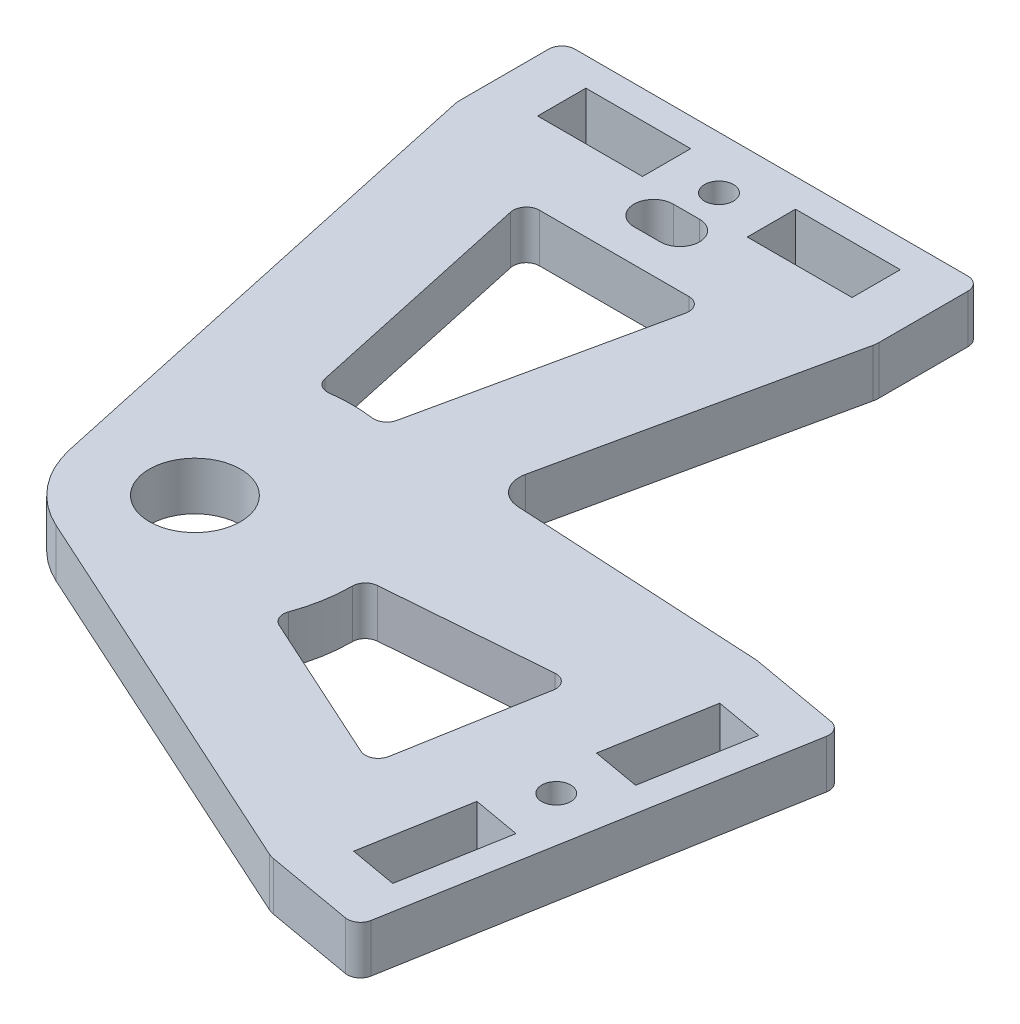
SolidWorks part; units mm, degrees
ref_plane "Front Plane" through (0, 0, 0) normal (0, 0, 1) x (1, 0, 0)
ref_plane "Top Plane" through (0, 0, 0) normal (0, 1, 0) x (1, 0, 0)
ref_plane "Right Plane" through (0, 0, 0) normal (1, 0, 0) x (0, 0, -1)
sketch "Sketch1" plane through (0, 0, 0) normal (0, 1, 0) x (1, 0, 0)
  line L0 (0, 0) -> (53.155, -9.3727) construction
  line L1 (0, 0) -> (0, 63.5) construction
  line L2 (12.7, 63.5) -> (-12.7, 63.5) construction
  line L3 (6.35, 63.5) -> (19.05, 63.5) construction
  line L4 (-6.35, 60.579) -> (-19.05, 60.579)
  line L5 (-6.35, 60.579) -> (-6.35, 66.421)
  line L6 (-6.35, 66.421) -> (-19.05, 66.421)
  line L7 (-19.05, 60.579) -> (-19.05, 66.421)
  line L8 (-12.7, 66.421) -> (-12.7, 60.579) construction
  line L9 (-6.35, 63.5) -> (-19.05, 63.5) construction
  line L10 (12.7, 66.421) -> (12.7, 60.579) construction
  line L11 (19.05, 60.579) -> (19.05, 66.421)
  line L12 (6.35, 66.421) -> (19.05, 66.421)
  line L13 (6.35, 60.579) -> (6.35, 66.421)
  line L14 (6.35, 60.579) -> (19.05, 60.579)
  line L15 (50.9497, -21.8797) -> (55.3603, 3.1344) construction
  line L16 (53.6034, 9.9916) -> (51.364, -2.7084)
  line L17 (53.6034, 9.9916) -> (59.3566, 8.9772)
  line L18 (51.364, -2.7084) -> (57.1173, -3.7228)
  line L19 (59.3566, 8.9772) -> (57.1173, -3.7228)
  line L20 (53.6034, 9.9916) -> (57.1173, -3.7228) construction
  line L21 (51.364, -2.7084) -> (59.3566, 8.9772) construction
  line L22 (49.1927, -15.0225) -> (52.7066, -28.7369) construction
  line L23 (46.9534, -27.7225) -> (54.946, -16.0369) construction
  line L24 (52.7066, -28.7369) -> (54.946, -16.0369)
  line L25 (49.1927, -15.0225) -> (54.946, -16.0369)
  line L26 (46.9534, -27.7225) -> (52.7066, -28.7369)
  line L27 (46.9534, -27.7225) -> (49.1927, -15.0225)
  line L28 (-25.4, 57.15) -> (-12.411, -2.6938)
  line L29 (-4.0407, 18.6165) -> (-11.026, 50.8)
  line L30 (25.4, 57.15) -> (25.4, 69.85)
  line L31 (25.4, 69.85) -> (-25.4, 69.85)
  line L32 (-25.4, 57.15) -> (-25.4, 69.85)
  line L33 (0, 69.85) -> (0, 63.5) construction
  line L34 (25.4, 63.5) -> (-25.4, 63.5) construction
  line L35 (25.4, 57.15) -> (17.0312, 18.5928)
  line L36 (4.0407, 18.6165) -> (11.026, 50.8)
  line L37 (-11.026, 50.8) -> (11.026, 50.8)
  line L38 (54.9979, -35.4894) -> (63.8192, 14.5388)
  line L39 (54.9979, -35.4894) -> (42.4908, -33.2841)
  line L40 (63.8192, 14.5388) -> (51.3121, 16.7441)
  line L42 (54.9979, -35.4894) -> (51.3121, 16.7441) construction
  line L43 (63.8192, 14.5388) -> (42.4908, -33.2841) construction
  line L44 (42.4908, -33.2841) -> (-5.2592, -11.5599)
  line L45 (51.3121, 16.7441) -> (17.0312, 18.5928)
  line L46 (17.3398, -7.8889) -> (38.7992, -17.652)
  line L47 (18.9922, 1.4826) -> (42.4967, 3.3173)
  line L48 (38.7992, -17.652) -> (42.4967, 3.3173)
  circle A0 centre (0, 0) radius 5.5245
  arc A1 (-12.411, -2.6938) -> (-5.2592, -11.5599) centre (0, 0) ccw
  circle A2 centre (0, 63.5) radius 1.7526
  circle A3 centre (53.155, -9.3727) radius 1.7526
  arc A4 (-4.0407, 18.6165) -> (4.0407, 18.6165) centre (0, 0) cw
  arc A5 (18.9922, 1.4826) -> (17.3398, -7.8889) centre (0, 0) cw
  point P9 (0, 63.5)
  point P27 (53.155, -9.3727)
  dimension "D1" = 11.049
  dimension "D2" = 25.4
  dimension "D9" = 3.5052
  dimension "D13" = 3.5052
  dimension "D16" = 19.05
  dimension "D21" = 19.05
  dimension "D3" = 53.975
  dimension "D4" = 100
  dimension "D5" = 63.5
  dimension "D6" = 25.4
  dimension "D7" = 5.842
  dimension "D8" = 12.7
  dimension "D10" = 25.4
  dimension "D11" = 5.842
  dimension "D12" = 12.7
  dimension "D14" = 50.8
  dimension "D15" = 12.7
  dimension "D17" = 12.7
  dimension "D18" = 12.7
  dimension "D19" = 12.7
  dimension "D20" = 50.8
  dimension "D22" = 12.7
  dimension "D23" = 12.7
extrude "Boss-Extrude1" add sketch "Sketch1" along normal blind 5.842
fillet "Fillet1" radius 1.5875 8 edges at (42.4967, 2.921, -3.3173) (38.7992, 2.921, 17.652) (17.3398, 2.921, 7.8889) (18.9922, 2.921, -1.4826) (11.026, 2.921, -50.8) (-11.026, 2.921, -50.8) (-4.0407, 2.921, -18.6165) (4.0407, 2.921, -18.6165)
fillet "Fillet2" radius 1.5875 4 edges at (-25.4, 2.921, -69.85) (25.4, 2.921, -69.85) (63.8192, 2.921, -14.5388) (54.9979, 2.921, 35.4894)
fillet "Fillet3" radius 3.175 5 edges at (-25.4, 2.921, -57.15) (25.4, 2.921, -57.15) (17.0312, 2.921, -18.5928) (42.4908, 2.921, 33.2841) (51.3121, 2.921, -16.7441)
sketch "Sketch2" plane through (0, 5.842, 0) normal (0, 1, 0) x (1, 0, 0)
  line L0 (0, 63.5461) -> (0, 50.8) construction
  line L1 (9.057, 50.8) -> (-9.057, 50.8) construction
  line L2 (1.5875, 57.173) -> (-1.5875, 57.173) construction
  line L3 (1.5875, 54.7918) -> (-1.5875, 54.7918)
  line L4 (1.5875, 59.5543) -> (-1.5875, 59.5543)
  arc A0 (1.5875, 54.7918) -> (1.5875, 59.5543) centre (1.5875, 57.173) ccw
  arc A1 (-1.5875, 59.5543) -> (-1.5875, 54.7918) centre (-1.5875, 57.173) ccw
  point P6 (0, 57.173)
  dimension "D2" = 2.3813
  dimension "D1" = 3.175
extrude "Cut-Extrude3" cut sketch "Sketch2" against normal through all
